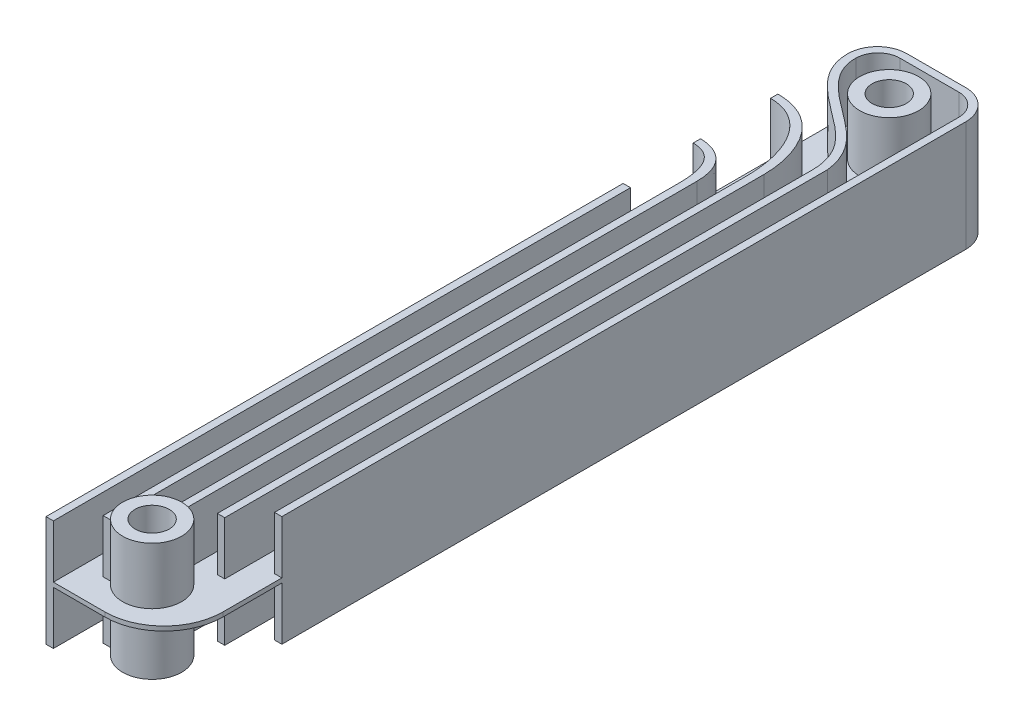
SolidWorks part; units mm, degrees
ref_plane "Спереди" through (0, 0, 0) normal (0, 0, 1) x (1, 0, 0)
ref_plane "Сверху" through (0, 0, 0) normal (0, 1, 0) x (1, 0, 0)
ref_plane "Справа" through (0, 0, 0) normal (1, 0, 0) x (0, 0, -1)
sketch "Эскиз1" plane through (0, 0, 0) normal (0, 1, 0) x (1, 0, 0)
  line L1 (0, 0) -> (40, 0)
  line L2 (0, 0) -> (0, 544)
  line L3 (20, 564) -> (60, 564)
  line L4 (80, 40) -> (80, 544)
  arc A0 (80, 544) -> (60, 564) centre (60, 544) ccw
  arc A1 (0, 544) -> (20, 564) centre (20, 544) cw
  arc A2 (80, 40) -> (40, 0) centre (40, 40) cw
  point P7 (80, 564)
  point P12 (80, 0)
  dimension "D3" = 20
  dimension "D4" = 40
  dimension "D1" = 564
  dimension "D2" = 80
extrude "Бобышка-Вытянуть1" add sketch "Эскиз1" along normal mid plane 3
sketch "Эскиз4" plane through (0, 0, 0) normal (0, 1, 0) x (1, 0, 0)
  line L1 (60, 564) -> (20, 564) construction
  line L2 (40, 32) -> (40, 0) construction
  line L3 (40, 532) -> (40, 564) construction
  circle A0 centre (40, 532) radius 20
  circle A1 centre (40, 32) radius 20
  dimension "D2" = 40
  dimension "D1" = 500
extrude "Бобышка-Вытянуть3" add sketch "Эскиз4" along normal mid plane 80
sketch "Эскиз3" plane through (0, 0, 0) normal (0, 1, 0) x (1, 0, 0)
  line L0 (5, 0) -> (5, 391.5128)
  line L1 (5, 391.5128) -> (0, 391.5128)
  line L2 (18.75, 20) -> (18.75, 410.9606)
  line L3 (18.75, 20) -> (23.75, 20)
  line L4 (0, 544) -> (0, 0)
  line L5 (0, 0) -> (40, 0)
  line L6 (80, 40) -> (80, 544)
  line L7 (60, 564) -> (20, 564)
  line L8 (0, 391.5128) -> (0, 0)
  line L9 (0, 0) -> (5, 0)
  line L12 (23.75, 20) -> (23.75, 418.0325)
  line L13 (37.5, 437.4803) -> (37.5, 40)
  line L14 (37.5, 40) -> (42.5, 40)
  line L15 (42.5, 40) -> (42.5, 444.5522)
  line L17 (75, 544) -> (75, 80)
  line L18 (75, 80) -> (80, 80)
  line L19 (56.25, 464) -> (56.25, 60)
  line L20 (56.25, 60) -> (61.25, 60)
  line L21 (61.25, 60) -> (61.25, 469.0335)
  line L22 (60, 564) -> (20, 564) construction
  line L23 (60, 564) -> (20, 564)
  line L24 (5, 391.5128) -> (18.75, 410.9606) construction
  line L25 (42.5, 444.5522) -> (56.25, 464) construction
  line L26 (0, 0) -> (40, 0) construction
  line L27 (80, 80) -> (80, 544)
  line L28 (80, 40) -> (80, 544) construction
  line L29 (5, 0) -> (18.75, 20) construction
  line L30 (23.75, 20) -> (37.5, 40) construction
  line L31 (42.5, 40) -> (56.25, 60) construction
  line L32 (61.25, 60) -> (75, 80) construction
  line L35 (23.75, 418.0325) -> (37.5, 437.4803) construction
  line L36 (60.3287, 559) -> (20.3287, 559)
  line L46 (0, 544) -> (0, 0) construction
  line L47 (0, 491.5043) -> (0, 496.5043)
  line L48 (0, 444.0086) -> (0, 439.0086)
  line L49 (0, 544) -> (0, 496.5043) construction
  line L50 (0, 491.5043) -> (0, 444.0086) construction
  line L51 (0, 439.0086) -> (0, 391.5128) construction
  line L52 (-8.5716, 439.2149) -> (8.5716, 438.8022) construction
  line L53 (-11.7617, 444.2918) -> (11.7617, 443.7254) construction
  line L54 (23.6709, 431.2735) -> (23.8291, 404.7911) construction
  line L55 (18.6455, 428.4509) -> (18.8545, 393.4703) construction
  line L56 (37.5, 460.666) -> (37.5, 412.2696) construction
  line L57 (42.5, 462.1126) -> (42.5, 423.7884) construction
  line L58 (-14.2275, 496.5043) -> (14.2275, 496.5043) construction
  line L59 (-14.2331, 491.5043) -> (14.2331, 491.5043) construction
  arc A0 (80, 544) -> (60, 564) centre (60, 544) ccw construction
  arc A1 (80, 544) -> (60, 564) centre (60, 544) ccw
  arc A2 (20, 564) -> (0, 544) centre (20, 544) ccw construction
  arc A3 (40, 0) -> (80, 40) centre (40, 40) ccw
  arc A4 (80, 544) -> (60, 564) centre (60, 544) ccw
  arc A5 (20, 564) -> (0, 544) centre (20, 544) ccw
  arc A6 (20, 564) -> (0, 544) centre (20, 544) ccw
  arc A9 (60.3287, 559) -> (75, 544) centre (60.1681, 544.168) cw
  arc A11 (20.3287, 559) -> (5.3287, 543.9773) centre (20.3287, 544) ccw
  spline S0 degree 3 poles (56.25, 464) (55.8882, 484.4306) (40.3286, 495.3377) (11.678, 517.0662) (-0.1428, 529.4162) (0, 544) knots 0 0 0 0 0.386951 0.462925 0.759744 0.759744 0.759744 0.759744
  spline S3 degree 3 poles (42.5, 444.5522) (42.5, 468.5048) (29.9243, 496.5043) (0, 496.5043) knots 0 0 0 0 0.660697 0.660697 0.660697 0.660697
  spline S4 degree 3 poles (5.3287, 543.9773) (5.3241, 543.506) (5.3374, 542.5516) (5.4577, 540.7378) (5.7724, 538.5575) (6.395, 536.076) (7.5342, 532.9025) (9.5153, 529.1348) (12.715, 524.8254) (16.6281, 520.6843) (22.5997, 515.3449) (31.0357, 508.8727) (39.4561, 502.6864) (45.8061, 497.3357) (50.245, 492.9623) (54.2154, 488.0683) (56.9801, 483.4411) (58.7656, 479.3694) (59.8691, 476.128) (60.5766, 473.2644) (61.007, 470.8832) (61.1777, 469.6479) (61.25, 469.0335) knots 0.029281 0.029281 0.029281 0.029281 0.040698 0.052114 0.074946 0.097779 0.120611 0.166276 0.211941 0.257606 0.303271 0.394601 0.485931 0.531596 0.577261 0.622926 0.668591 0.691424 0.714256 0.737089 0.748505 0.759922 0.759922 0.759922 0.759922
  spline S5 degree 3 poles (23.75, 418.0325) (23.6511, 434.5841) (14.7021, 443.6546) (0, 444.0086) knots 0 0 0 0 0.451095 0.451095 0.451095 0.451095
  spline S6 degree 3 poles (37.5, 437.4803) (37.5, 467.728) (23.5661, 491.5043) (0, 491.5043) knots 0 0 0 0 0.558747 0.558747 0.558747 0.558747
  spline S7 degree 3 poles (18.75, 410.9606) (18.6193, 432.8235) (10.7145, 438.7506) (0, 439.0086) knots 0 0 0 0 0.38331 0.38331 0.38331 0.38331
  point P29 (0, 0)
  point P31 (0, 0)
  point P32 (0, 0)
  dimension "D2" = 5
  dimension "D3" = 80
  dimension "D5" = 5
  dimension "D1" = 0
extrude "Бобышка-Вытянуть2" add sketch "Эскиз3" along normal mid plane 75
sketch "Эскиз5" plane through (0, 0, 0) normal (0, 1, 0) x (1, 0, 0)
  circle A0 centre (40, 32) radius 20 construction
  circle A1 centre (40, 32) radius 20 construction
  circle A2 centre (40, 532) radius 20 construction
  circle A3 centre (40, 532) radius 20 construction
  circle A4 centre (40, 532) radius 11.6086
  circle A5 centre (40, 32) radius 11.6086
  dimension "D1" = 23.2171
extrude "Вырез-Вытянуть1" cut sketch "Эскиз5" against normal through all both and the other way through all
